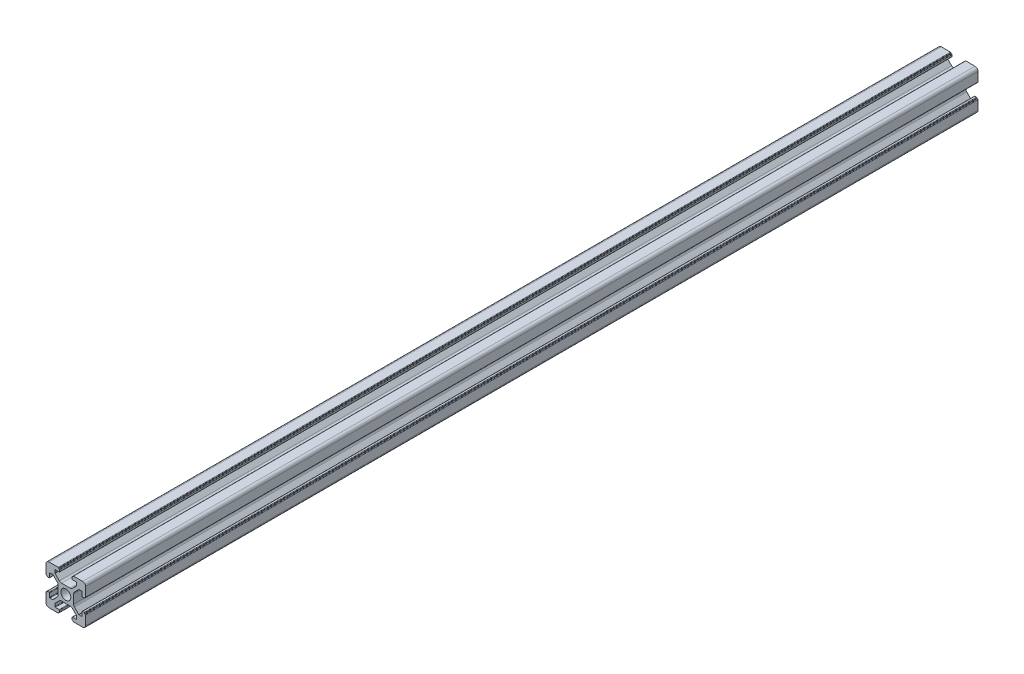
SolidWorks part; units mm, degrees
ref_plane "前视基准面" through (0, 0, 0) normal (0, 0, 1) x (1, 0, 0)
ref_plane "上视基准面" through (0, 0, 0) normal (0, 1, 0) x (1, 0, 0)
ref_plane "右视基准面" through (0, 0, 0) normal (1, 0, 0) x (0, 0, -1)
sketch "草图1" plane through (0, 0, 0) normal (0, 0, 1) x (1, 0, 0)
  line L0 (0, 0) -> (0, 5.5) construction
  line L1 (-8.5023, -10.0023) -> (-3.85, -10.0023)
  line L2 (-10.0023, -8.5023) -> (-10.0023, -3.85)
  line L3 (-8.5023, 10.0023) -> (-3.85, 10.0023)
  line L4 (10.0023, -8.5023) -> (10.0023, -3.85)
  line L5 (-10.0023, -10.0023) -> (10.0023, 10.0023) construction
  line L6 (-10.0023, 10.0023) -> (10.0023, -10.0023) construction
  line L7 (-2.218, -3.9) -> (2.218, -3.9)
  line L8 (-3.9, -2.218) -> (-3.9, 2.218)
  line L9 (-2.218, 3.9) -> (2.218, 3.9)
  line L10 (3.9, -2.218) -> (3.9, 2.218)
  line L11 (-3.9, -3.9) -> (3.9, 3.9) construction
  line L12 (-3.9, 3.9) -> (3.9, -3.9) construction
  line L13 (-5.25, -8.2) -> (-3.35, -8.2)
  line L14 (-8.2, -5.25) -> (-8.2, -3.35)
  line L15 (-5.25, 8.2) -> (-3.35, 8.2)
  line L16 (8.2, -5.25) -> (8.2, -3.35)
  line L17 (-8.2, -8.2) -> (8.2, 8.2) construction
  line L18 (-8.2, 8.2) -> (8.2, -8.2) construction
  line L19 (-7.95, 5.5) -> (-6.6642, 5.5)
  line L20 (0, 0) -> (5.5, 0) construction
  line L23 (-5.5, 7.95) -> (-5.5, 6.6642)
  line L26 (0, 0) -> (-0.5303, 0.5303)
  line L27 (3.2787, 4.3393) -> (5.4268, 6.4874)
  line L28 (0, 0) -> (0.5303, -0.5303)
  line L29 (5.5, 6.6642) -> (5.5, 7.95)
  line L30 (4.3393, 3.2787) -> (6.4874, 5.4268)
  line L31 (6.6642, 5.5) -> (7.95, 5.5)
  line L32 (4.3393, -3.2787) -> (6.4874, -5.4268)
  line L33 (3.2787, -4.3393) -> (5.4268, -6.4874)
  line L34 (-3.2787, -4.3393) -> (-5.4268, -6.4874)
  line L35 (-4.3393, -3.2787) -> (-6.4874, -5.4268)
  line L36 (-4.3393, 3.2787) -> (-6.4874, 5.4268)
  line L37 (-3.2787, 4.3393) -> (-5.4268, 6.4874)
  line L38 (3.1, -8.45) -> (3.1, -9.2523)
  line L39 (8.45, 3.1) -> (9.2523, 3.1)
  line L40 (-5.5, -6.6642) -> (-5.5, -7.95)
  line L41 (-6.6642, -5.5) -> (-7.95, -5.5)
  line L42 (5.5, -6.6642) -> (5.5, -7.95)
  line L43 (6.6642, -5.5) -> (7.95, -5.5)
  line L44 (9.2523, -3.1) -> (8.45, -3.1)
  line L46 (10.0023, 3.85) -> (10.0023, 8.5023)
  line L47 (8.2, 3.35) -> (8.2, 5.25)
  line L48 (-3.1, -9.2523) -> (-3.1, -8.45)
  line L49 (-8.45, -3.1) -> (-9.2523, -3.1)
  line L50 (-9.2523, 3.1) -> (-8.45, 3.1)
  line L51 (-3.1, 8.45) -> (-3.1, 9.2523)
  line L52 (3.1, 9.2523) -> (3.1, 8.45)
  line L53 (3.85, 10.0023) -> (8.5023, 10.0023)
  line L54 (3.35, 8.2) -> (5.25, 8.2)
  line L55 (-10.0023, 3.85) -> (-10.0023, 8.5023)
  line L56 (-8.2, 3.35) -> (-8.2, 5.25)
  line L57 (3.35, -8.2) -> (5.25, -8.2)
  line L58 (3.85, -10.0023) -> (8.5023, -10.0023)
  line L59 (9.7523, -3.6) -> (9.5023, -3.6)
  line L61 (9.7523, 3.6) -> (9.5023, 3.6)
  line L62 (9.5023, -3.6) -> (9.5023, -3.35)
  line L63 (3.6, -9.7523) -> (3.6, -9.5023)
  line L64 (3.35, -9.5023) -> (3.6, -9.5023)
  line L65 (9.5023, 3.35) -> (9.5023, 3.6)
  line L66 (-3.6, -9.5023) -> (-3.35, -9.5023)
  line L67 (-3.6, -9.7523) -> (-3.6, -9.5023)
  line L68 (-9.7523, -3.6) -> (-9.5023, -3.6)
  line L69 (-9.5023, -3.35) -> (-9.5023, -3.6)
  line L70 (-9.5023, 3.6) -> (-9.5023, 3.35)
  line L71 (-9.7523, 3.6) -> (-9.5023, 3.6)
  line L72 (-3.6, 9.7523) -> (-3.6, 9.5023)
  line L73 (-3.35, 9.5023) -> (-3.6, 9.5023)
  line L74 (3.6, 9.5023) -> (3.35, 9.5023)
  line L75 (3.6, 9.7523) -> (3.6, 9.5023)
  circle A0 centre (0, 0) radius 2.5
  arc A1 (10.0023, 8.5023) -> (8.5023, 10.0023) centre (8.5023, 8.5023) ccw
  arc A2 (8.5023, -10.0023) -> (10.0023, -8.5023) centre (8.5023, -8.5023) ccw
  arc A3 (-10.0023, -8.5023) -> (-8.5023, -10.0023) centre (-8.5023, -8.5023) ccw
  arc A4 (-10.0023, 8.5023) -> (-8.5023, 10.0023) centre (-8.5023, 8.5023) cw
  arc A5 (-9.5023, -3.35) -> (-9.2523, -3.1) centre (-9.2523, -3.35) cw
  arc A6 (-9.7523, -3.6) -> (-10.0023, -3.85) centre (-9.7523, -3.85) ccw
  arc A7 (-8.45, -3.1) -> (-8.2, -3.35) centre (-8.45, -3.35) cw
  arc A8 (-7.95, -5.5) -> (-8.2, -5.25) centre (-7.95, -5.25) cw
  arc A9 (-6.4874, -5.4268) -> (-6.6642, -5.5) centre (-6.6642, -5.25) cw
  arc A10 (-5.4268, -6.4874) -> (-5.5, -6.6642) centre (-5.25, -6.6642) ccw
  arc A11 (-5.5, -7.95) -> (-5.25, -8.2) centre (-5.25, -7.95) ccw
  arc A12 (-3.6, -9.7523) -> (-3.85, -10.0023) centre (-3.85, -9.7523) cw
  arc A13 (-3.35, -9.5023) -> (-3.1, -9.2523) centre (-3.35, -9.2523) ccw
  arc A14 (-3.1, -8.45) -> (-3.35, -8.2) centre (-3.35, -8.45) ccw
  arc A15 (3.1, -8.45) -> (3.35, -8.2) centre (3.35, -8.45) cw
  arc A16 (5.5, -7.95) -> (5.25, -8.2) centre (5.25, -7.95) cw
  arc A17 (5.4268, -6.4874) -> (5.5, -6.6642) centre (5.25, -6.6642) cw
  arc A18 (6.4874, -5.4268) -> (6.6642, -5.5) centre (6.6642, -5.25) ccw
  arc A19 (7.95, -5.5) -> (8.2, -5.25) centre (7.95, -5.25) ccw
  arc A20 (8.45, -3.1) -> (8.2, -3.35) centre (8.45, -3.35) ccw
  arc A21 (9.5023, -3.35) -> (9.2523, -3.1) centre (9.2523, -3.35) ccw
  arc A22 (9.7523, -3.6) -> (10.0023, -3.85) centre (9.7523, -3.85) cw
  arc A23 (3.35, -9.5023) -> (3.1, -9.2523) centre (3.35, -9.2523) cw
  arc A24 (3.6, -9.7523) -> (3.85, -10.0023) centre (3.85, -9.7523) ccw
  arc A25 (7.95, 5.5) -> (8.2, 5.25) centre (7.95, 5.25) cw
  arc A26 (8.2, 3.35) -> (8.45, 3.1) centre (8.45, 3.35) ccw
  arc A27 (9.5023, 3.35) -> (9.2523, 3.1) centre (9.2523, 3.35) cw
  arc A28 (9.7523, 3.6) -> (10.0023, 3.85) centre (9.7523, 3.85) ccw
  arc A29 (6.6642, 5.5) -> (6.4874, 5.4268) centre (6.6642, 5.25) ccw
  arc A30 (5.4268, 6.4874) -> (5.5, 6.6642) centre (5.25, 6.6642) ccw
  arc A31 (5.5, 7.95) -> (5.25, 8.2) centre (5.25, 7.95) ccw
  arc A32 (3.1, 8.45) -> (3.35, 8.2) centre (3.35, 8.45) ccw
  arc A33 (3.6, 9.7523) -> (3.85, 10.0023) centre (3.85, 9.7523) cw
  arc A34 (3.35, 9.5023) -> (3.1, 9.2523) centre (3.35, 9.2523) ccw
  arc A35 (-9.7523, 3.6) -> (-10.0023, 3.85) centre (-9.7523, 3.85) cw
  arc A36 (-9.5023, 3.35) -> (-9.2523, 3.1) centre (-9.2523, 3.35) ccw
  arc A37 (-8.45, 3.1) -> (-8.2, 3.35) centre (-8.45, 3.35) ccw
  arc A38 (-8.2, 5.25) -> (-7.95, 5.5) centre (-7.95, 5.25) cw
  arc A39 (-6.4874, 5.4268) -> (-6.6642, 5.5) centre (-6.6642, 5.25) ccw
  arc A40 (-5.4268, 6.4874) -> (-5.5, 6.6642) centre (-5.25, 6.6642) cw
  arc A41 (-5.5, 7.95) -> (-5.25, 8.2) centre (-5.25, 7.95) cw
  arc A42 (-3.1, 8.45) -> (-3.35, 8.2) centre (-3.35, 8.45) cw
  arc A43 (-3.1, 9.2523) -> (-3.35, 9.5023) centre (-3.35, 9.2523) ccw
  arc A44 (-3.6, 9.7523) -> (-3.85, 10.0023) centre (-3.85, 9.7523) ccw
  arc A45 (-4.3393, 3.2787) -> (-3.9, 2.218) centre (-5.4, 2.218) cw
  arc A46 (-3.2787, 4.3393) -> (-2.218, 3.9) centre (-2.218, 5.4) ccw
  arc A47 (3.2787, 4.3393) -> (2.218, 3.9) centre (2.218, 5.4) cw
  arc A48 (4.3393, 3.2787) -> (3.9, 2.218) centre (5.4, 2.218) ccw
  arc A49 (4.3393, -3.2787) -> (3.9, -2.218) centre (5.4, -2.218) cw
  arc A50 (3.2787, -4.3393) -> (2.218, -3.9) centre (2.218, -5.4) ccw
  arc A51 (-4.3393, -3.2787) -> (-3.9, -2.218) centre (-5.4, -2.218) ccw
  arc A52 (-2.218, -3.9) -> (-3.2787, -4.3393) centre (-2.218, -5.4) ccw
  point P0 (0, 0)
  point P7 (10.0023, 0)
  point P62 (0, 0)
  point P76 (0, 0)
  point P92 (-8.2, -5.5)
  point P99 (0, 0)
  point P106 (-5.5, -8.2)
  point P117 (5.5, -8.2)
  point P124 (8.2, -5.5)
  point P137 (8.2, 5.5)
  point P140 (8.2, 3.1)
  point P147 (6.5607, 5.5)
  point P152 (5.5, 8.2)
  point P167 (-8.2, 5.5)
  point P174 (-5.5, 8.2)
  dimension "D1" = 1.5
  dimension "D5" = 0.25
  dimension "D6" = 1.5
  dimension "D2" = 4
  dimension "D3" = 4
  dimension "D4" = 4
extrude "凸台-拉伸1" add sketch "草图1" along normal mid plane 450 contours A52 L7 A50 L33 A17 L42 A16 L57 A15 L38 A23 L64 L63 A24 L58 A2 L4 A22 L59 L62 A21 L44 A20 L16 A19 L43 A18 L32 A49 L10 A48 L30 A29 L31 A25 L47 A26 L39 A27 L65 L61 A28 L46 A1 L53 A33 L75 L74 A34 L52 A32
